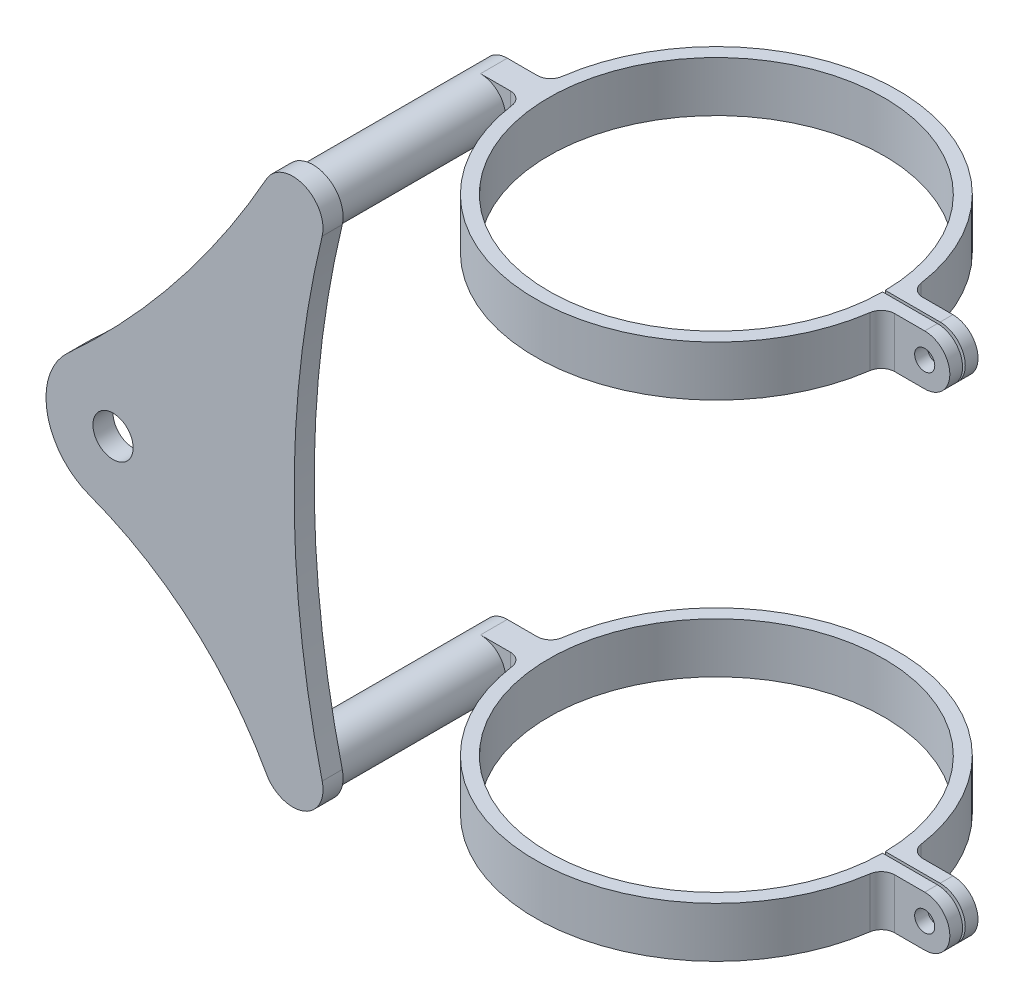
SolidWorks part; units mm, degrees
material "6061-T6 (SS)"
ref_plane "Front Plane" through (0, 0, 0) normal (1, 0, 0) x (0, 1, 0)
ref_plane "Top Plane" through (0, 0, 0) normal (0, 0, 1) x (0, 1, 0)
ref_plane "Right Plane" through (0, 0, 0) normal (0, 1, 0) x (-1, 0, 0)
sketch "Sketch1" plane through (0, 0, 0) normal (0, 1, 0) x (-1, 0, 0)
  line L0 (-50.7151, 0) -> (71.469, 0) construction
  line L1 (0, 41.4675) -> (0, -37.8609) construction
  line L2 (-36.93, 2.1) -> (-28.7087, 2.1)
  line L3 (-36.93, 0.2) -> (-24.9992, 0.2)
  line L4 (-36.93, -0.2) -> (-24.9992, -0.2)
  line L5 (-36.93, -2.1) -> (-28.7087, -2.1)
  line L6 (-36.93, 2.1) -> (-36.93, 0.2)
  line L7 (-36.93, -0.2) -> (-36.93, -2.1)
  line L9 (28.7228, 2) -> (33.18, 2)
  line L11 (28.7228, -2) -> (33.18, -2)
  line L12 (33.18, 2) -> (33.18, -2)
  arc A1 (-24.9992, -0.2) -> (-24.9992, 0.2) centre (0, 0) ccw
  arc A2 (-26.7288, -3.8172) -> (26.7419, -3.7241) centre (0, 0) ccw
  arc A3 (26.7419, -3.7241) -> (28.7228, -2) centre (28.7228, -4) cw
  arc A4 (26.7419, 3.7241) -> (28.7228, 2) centre (28.7228, 4) ccw
  arc A5 (26.7419, 3.7241) -> (-26.7288, 3.8172) centre (0, 0) ccw
  arc A6 (-26.7288, -3.8172) -> (-28.7087, -2.1) centre (-28.7087, -4.1) ccw
  arc A7 (-28.7087, 2.1) -> (-26.7288, 3.8172) centre (-28.7087, 4.1) ccw
  point P1 (33.18, 0)
  dimension "D1" = 50
  dimension "D2" = 27
  dimension "D7" = 2
  dimension "D9" = 2
  dimension "D3" = 0.2
  dimension "D4" = 1.9
  dimension "D5" = 36.93
  dimension "D6" = 4
  dimension "D8" = 33.18
extrude "Boss-Extrude1" add sketch "Sketch1" against normal mid plane 7.5
sketch "Sketch2" plane through (0, 0, 2.1) normal (0, 0, 1) x (1, 0, 0)
  line L0 (28.7087, -3.75) -> (36.93, -3.75) construction
  line L1 (36.93, -3.75) -> (36.93, 3.75) construction
  line L6 (36.93, 3.75) -> (28.7087, 3.75)
  line L7 (28.7087, 3.75) -> (28.7087, -3.75)
  line L8 (28.7087, -3.75) -> (36.93, -3.75)
  line L9 (36.93, -3.75) -> (36.93, 3.75)
  line L10 (36.93, 3.75) -> (28.7087, 3.75)
  line L12 (28.7087, -3.75) -> (36.93, -3.75)
  line L13 (36.93, -3.75) -> (36.93, 3.75)
  line L14 (28.7087, 3.75) -> (28.7087, -3.75)
  circle A0 centre (33.18, 0) radius 3.75
  circle A1 centre (33.18, 0) radius 1.5
  line M5 (36.93, 3.75) -> (28.7087, 3.75)
  line M8 (36.93, -3.75) -> (36.93, 3.75)
  dimension "D1" = 3
  dimension "D2" = 7.5
  dimension "D3" = 0
extrude "Cut-Extrude1" cut sketch "Sketch2" against normal through all both and the other way through all contours A0 L13 M5 | A0 L12 M8 | A1
sketch "Sketch3" plane through (0, 0, 2) normal (0, 0, 1) x (1, 0, 0)
  line L1 (-33.18, -3.75) -> (-28.7228, -3.75) construction
  circle A0 centre (-33.17, 0) radius 3.75
  circle A2 centre (33.18, 0) radius 1.5 construction
  dimension "D1" = 7.5
  dimension "D2" = 66.35
extrude "Boss-Extrude2" add sketch "Sketch3" along normal blind 29 from surface at -4 starting at face at (-30.9514, 0, -2)
move or copy body "Body-Move/Copy1" bodies to move or copy 104 copy yes number of copies 1 translate (0, -72.5, 0) parameters "D1"=0, "D2"=72.5, "D3"=0
sketch "Sketch4" plane through (0, 0, 27) normal (0, 0, 1) x (1, 0, 0)
  line L0 (-28.7228, -3.75) -> (-28.7228, 3.75) construction
  arc A0 (-37.115, -74.665) -> (-28.7956, -71.4442) centre (-33.17, -72.5) ccw
  circle A1 centre (-33.17, -72.5) radius 3.75 construction
  arc A2 (-37.115, -74.665) -> (-63.483, -51.8701) centre (-80.9479, -98.7207) ccw
  arc A3 (-63.483, -51.8701) -> (-66.7333, -35.1157) centre (-59.99, -42.5) cw
  circle A4 centre (-59.99, -42.5) radius 3
  circle A6 centre (33.18, 0) radius 1.5 construction
  arc A7 (-28.7956, -1.0558) -> (-37.0937, 2.2034) centre (-33.17, 0) ccw
  circle A8 centre (-33.17, 0) radius 3.75 construction
  arc A9 (-66.7333, -35.1157) -> (-37.0937, 2.2034) centre (-167.8826, 75.649) ccw
  arc A10 (-28.7956, -71.4442) -> (-28.7228, -0.7556) centre (117.0172, -36.25) cw
  point P30 (-167.872, 75.6678)
  point P31 (-64.0452, -38.0687)
  point P32 (-33.6059, 0.2449)
  point P33 (117.0172, -36.25)
  point P34 (-31.5134, -72.5)
  point P35 (-32.6092, 0.191)
  circle M3 centre (-33.17, -72.5) radius 3.75
  dimension "D1" = 9
  dimension "D2" = 10
  dimension "D3" = 6
  dimension "D4" = 50
  dimension "D6" = 9
  dimension "D7" = 150
  dimension "D8" = 150
  dimension "D5" = 26.82
  dimension "D9" = 30
  dimension "D10" = 26.82
  dimension "D11" = 66.35
  dimension "D12" = 59.99
extrude "Boss-Extrude3" add sketch "Sketch4" along normal blind 3 contours A0 A10 A7 A9 A3 A2 A4 M3 | M3
sketch "Sketch5" plane through (0, 0, 27) normal (0, 0, -1) x (1, 0, 0)
  line L0 (-38.8842, 63.7526) -> (-36.8842, 63.7526)
  line L1 (-39.6223, 61.7526) -> (-36.4799, 61.7526) construction
  arc A0 (-59.8718, 36.5012) -> (-60.549, 34.7843) centre (-59.8521, 35.5014) ccw
  arc A1 (-57.8432, 49.9132) -> (-57.7832, 48.0794) centre (-57.4154, 49.0093) ccw
  arc A4 (-38.1678, 7.3574) -> (-34.5152, 8.792) centre (-36.4831, 8.4354) ccw
  arc A5 (-62.0858, 48.1221) -> (-33.6083, 72.7406) centre (-80.9479, 98.7207) ccw
  arc A6 (-57.8432, 49.9132) -> (-40.3864, 63.0728) centre (-80.9479, 98.7207) ccw
  arc A7 (-34.9111, 61.4256) -> (-36.8842, 63.7526) centre (-36.8842, 61.7526) ccw
  arc A8 (-33.606, -0.2448) -> (-64.036, 38.0694) centre (-167.8826, -75.649) ccw
  arc A9 (-38.1678, 7.3574) -> (-60.549, 34.7843) centre (-167.8826, -75.649) ccw
  arc A10 (-40.3864, 63.0728) -> (-38.8842, 63.7526) centre (-38.8842, 61.7526) cw
  arc A11 (-32.684, 72.3827) -> (-32.684, 0.1173) centre (117.0172, 36.25) ccw
  arc A12 (-34.9111, 61.4256) -> (-34.5152, 8.792) centre (117.0172, 36.25) ccw
  circle A14 centre (-59.99, 42.5) radius 6
  arc A15 (-59.8718, 36.5012) -> (-57.7832, 48.0794) centre (-59.99, 42.5) ccw
  dimension "D5" = 4
  dimension "D6" = 2
  dimension "D8" = 2
  dimension "D7" = 2
  dimension "D1" = 4
  dimension "D2" = 4
  dimension "D3" = 4
  dimension "D4" = 3
extrude "Cut-Extrude2" cut sketch "Sketch5" against normal blind 1
ref_plane "Plane1" through (0, -36.25, 0) normal (0, 1, 0) x (-1, 0, 0)
equation "\"D8@Sketch1\"=36.93-(7.5/2)"
